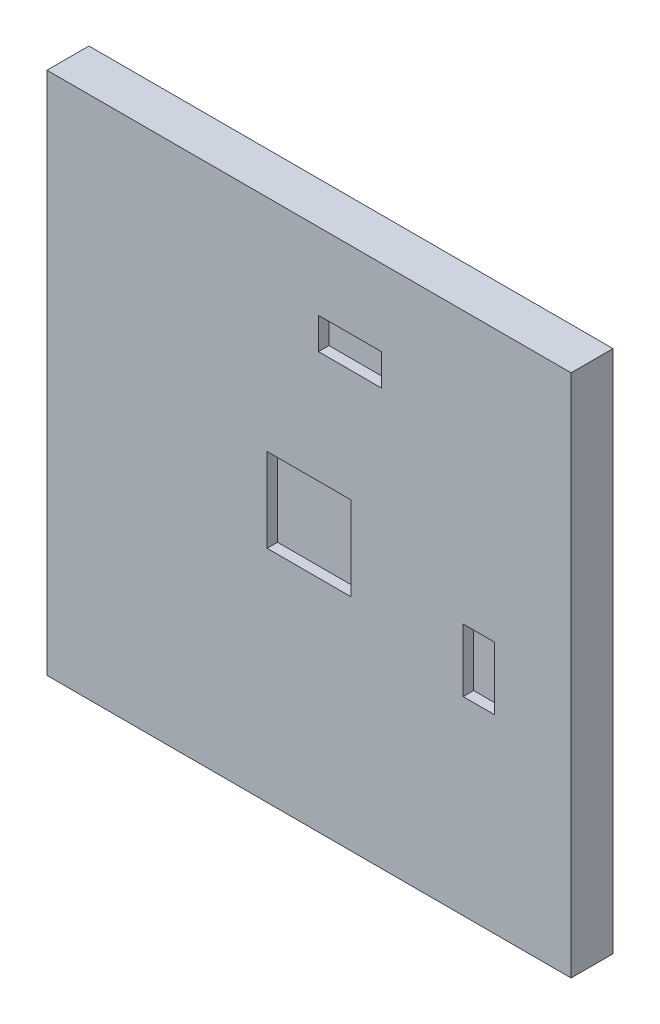
SolidWorks part; units mm, degrees
ref_plane "Ön Düzlem" through (0, 0, 0) normal (0, 0, 1) x (1, 0, 0)
ref_plane "Üst Düzlem" through (0, 0, 0) normal (0, 1, 0) x (1, 0, 0)
ref_plane "Sağ Düzlem" through (0, 0, 0) normal (1, 0, 0) x (0, 0, -1)
sketch "Sketch1" plane through (0, 0, 0) normal (0, 0, 1) x (1, 0, 0)
  line L1 (147.0484, -195.9037) -> (-102.9516, -195.9037)
  line L2 (147.0484, -195.9037) -> (147.0484, 54.0963)
  line L3 (147.0484, 54.0963) -> (-102.9516, 54.0963)
  line L4 (-102.9516, -195.9037) -> (-102.9516, 54.0963)
  dimension "D1" = 250
  dimension "D2" = 250
extrude "Boss-Extrude1" add sketch "Sketch1" along normal blind 20
sketch "Sketch2" plane through (0, 0, 20) normal (0, 0, 1) x (1, 0, 0)
  line L0 (147.0484, -195.9037) -> (147.0484, 54.0963) construction
  line L8 (110.5484, -105.4037) -> (110.5484, -90.4037)
  line L9 (2.0484, -50.9037) -> (42.0484, -50.9037)
  line L10 (2.0484, -50.9037) -> (2.0484, -90.9037)
  line L11 (2.0484, -90.9037) -> (42.0484, -90.9037)
  line L12 (42.0484, -50.9037) -> (42.0484, -90.9037)
  line L13 (-102.9516, -195.9037) -> (147.0484, -195.9037) construction
  line L14 (-102.9516, 54.0963) -> (-102.9516, -195.9037) construction
  line L16 (147.0484, 54.0963) -> (-102.9516, 54.0963) construction
  line L17 (110.5484, -105.4037) -> (95.5484, -105.4037)
  line L18 (110.5484, -105.4037) -> (110.5484, -75.4037)
  line L19 (110.5484, -75.4037) -> (95.5484, -75.4037)
  line L20 (95.5484, -105.4037) -> (95.5484, -75.4037)
  line L21 (56.5484, 17.5963) -> (26.5484, 17.5963)
  line L22 (56.5484, 17.5963) -> (56.5484, 2.5963)
  line L23 (56.5484, 2.5963) -> (26.5484, 2.5963)
  line L24 (26.5484, 17.5963) -> (26.5484, 2.5963)
  dimension "D2" = 36.5
  dimension "D3" = 30
  dimension "D4" = 15
  dimension "D5" = 40
  dimension "D6" = 40
  dimension "D8" = 36.5
  dimension "D10" = 105
  dimension "D11" = 105
  dimension "D13" = 15
  dimension "D14" = 30
extrude "Cut-Extrude2" cut sketch "Sketch2" against normal blind 5 contours L20 L17 L8 L18 L19 | L12 L9 L10 L11 | L21 L24 L23 L22
